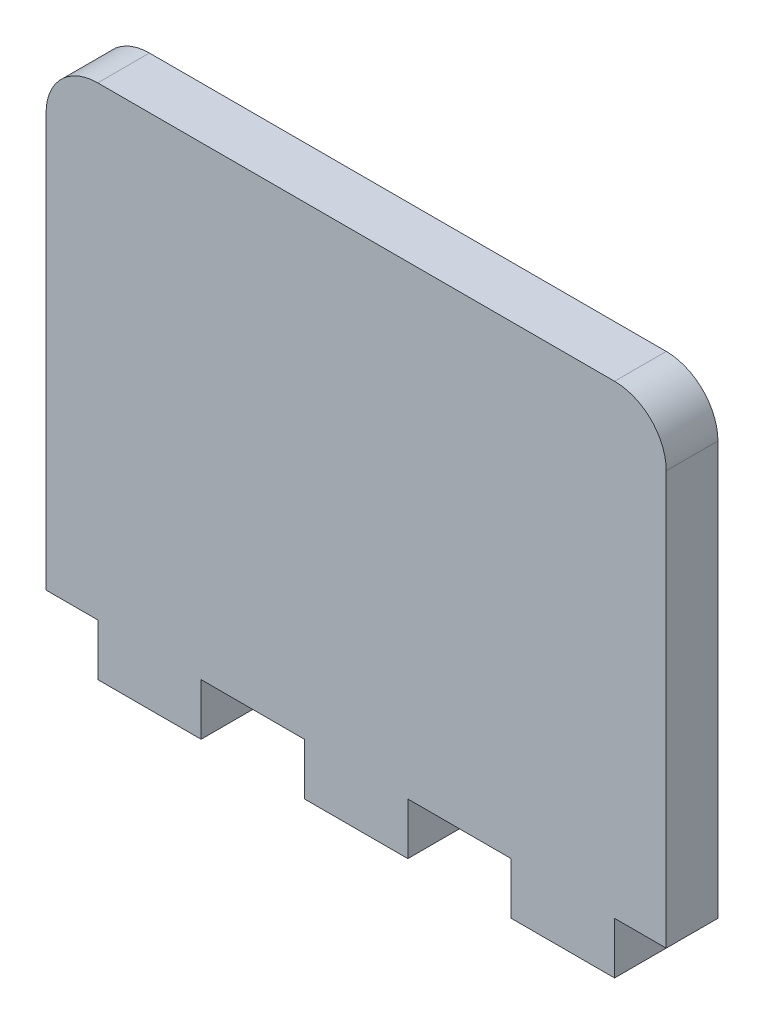
SolidWorks part; units mm, degrees
material "Acrylic (Medium-high impact)"
ref_plane "Front Plane" through (0, 0, 0) normal (0, 0, 1) x (1, 0, 0)
ref_plane "Top Plane" through (0, 0, 0) normal (0, 1, 0) x (1, 0, 0)
ref_plane "Right Plane" through (0, 0, 0) normal (1, 0, 0) x (0, 0, -1)
sketch "Sketch1" plane through (0, 0, 0) normal (0, 0, 1) x (1, 0, 0)
  line L0 (9.525, 0) -> (15.875, 0)
  line L1 (0, 0) -> (3.175, 0)
  line L2 (0, 0) -> (0, 28.575)
  line L3 (0, 28.575) -> (38.1, 28.575)
  line L4 (38.1, 0) -> (38.1, 28.575)
  line L5 (22.225, 0) -> (28.575, 0)
  line L6 (3.175, 0) -> (3.175, -3.175)
  line L7 (3.175, -3.175) -> (9.525, -3.175)
  line L8 (9.525, 0) -> (9.525, -3.175)
  line L9 (34.925, 0) -> (38.1, 0)
  line L10 (15.875, 0) -> (15.875, -3.175)
  line L11 (15.875, -3.175) -> (22.225, -3.175)
  line L12 (22.225, 0) -> (22.225, -3.175)
  line L14 (28.575, 0) -> (28.575, -3.175)
  line L15 (28.575, -3.175) -> (34.925, -3.175)
  line L16 (34.925, 0) -> (34.925, -3.175)
  dimension "D1" = 3.175
  dimension "D2" = 6.35
  dimension "D3" = 28.575
extrude "Boss-Extrude1" add sketch "Sketch1" along normal blind 3.175
fillet "Fillet1" radius 3.175 2 edges at (38.1, 28.575, 1.5875) (0, 28.575, 1.5875)
